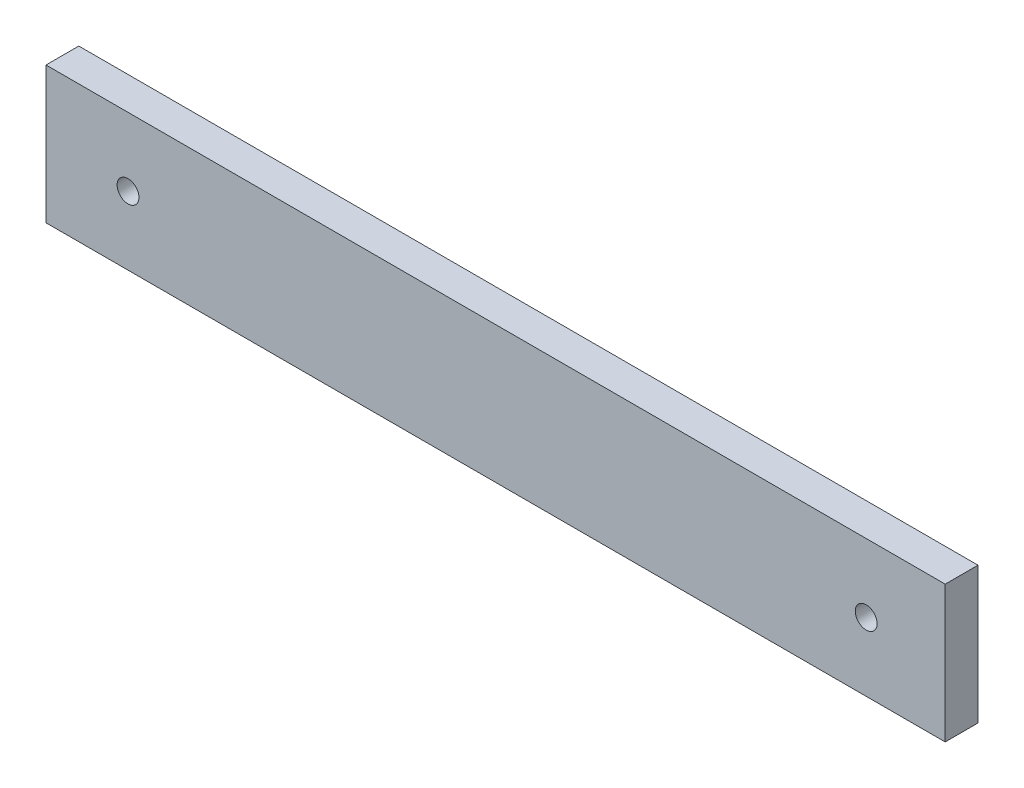
SolidWorks part; units mm, degrees
ref_plane "Front" through (0, 0, 0) normal (0, 0, 1) x (1, 0, 0)
ref_plane "Top" through (0, 0, 0) normal (0, 1, 0) x (1, 0, 0)
ref_plane "Right" through (0, 0, 0) normal (1, 0, 0) x (0, 0, -1)
sketch "Sketch1" plane through (0, 0, 0) normal (0, 0, 1) x (-1, 0, 0)
  line L0 (135, -2.5) -> (135, 22.5)
  line L1 (135, -2.5) -> (-29.449, -2.5)
  line L2 (135, 22.5) -> (-29.449, 22.5)
  line L3 (-29.449, -2.5) -> (-29.449, 22.5)
  circle A0 centre (-15, 10) radius 2
  circle A1 centre (120, 10) radius 2
extrude "Boss-Extrude1" add sketch "Sketch1" along normal blind 6
